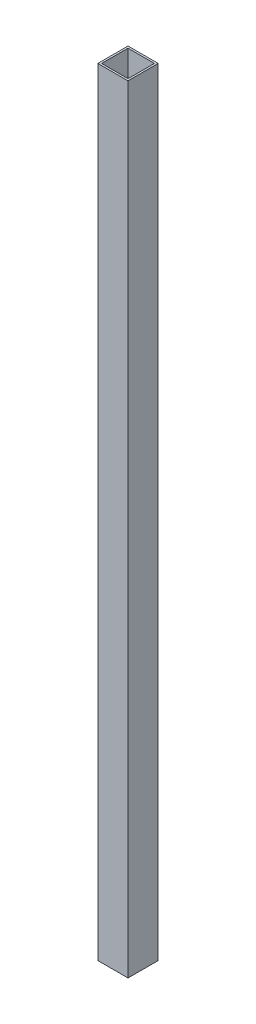
SolidWorks part; units mm, degrees
ref_plane "Front Plane" through (0, 0, 0) normal (0, 0, 1) x (1, 0, 0)
ref_plane "Top Plane" through (0, 0, 0) normal (0, 1, 0) x (1, 0, 0)
ref_plane "Right Plane" through (0, 0, 0) normal (1, 0, 0) x (0, 0, -1)
sketch "Sketch1" plane through (0, 0, 0) normal (0, 1, 0) x (1, 0, 0)
  line L1 (-11.1125, -11.1125) -> (11.1125, -11.1125)
  line L2 (-11.1125, -11.1125) -> (-11.1125, 11.1125)
  line L3 (-11.1125, 11.1125) -> (11.1125, 11.1125)
  line L4 (11.1125, -11.1125) -> (11.1125, 11.1125)
  line L5 (-11.1125, -11.1125) -> (11.1125, 11.1125) construction
  line L6 (-11.1125, 11.1125) -> (11.1125, -11.1125) construction
  line L7 (-12.7, -12.7) -> (12.7, -12.7)
  line L8 (-12.7, -12.7) -> (-12.7, 12.7)
  line L9 (-12.7, 12.7) -> (12.7, 12.7)
  line L10 (12.7, -12.7) -> (12.7, 12.7)
  line L11 (-12.7, -12.7) -> (12.7, 12.7) construction
  line L12 (-12.7, 12.7) -> (12.7, -12.7) construction
  point P0 (0, 0)
  point P6 (0, 0)
  dimension "D1" = 25.4
  dimension "D2" = 1.5875
extrude "Boss-Extrude1" add sketch "Sketch1" along normal blind 654.05
